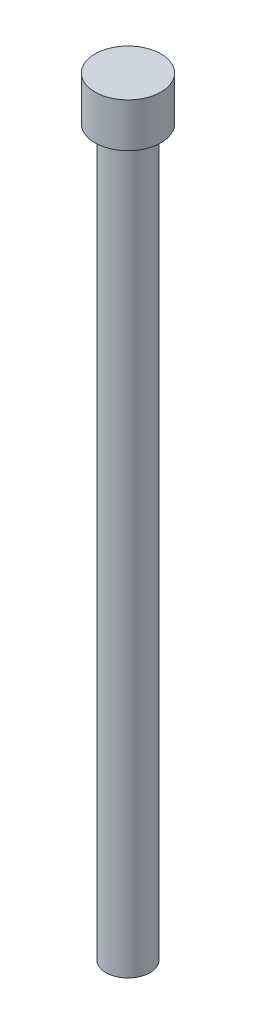
SolidWorks part; units mm, degrees
ref_plane "前视基准面" through (0, 0, 0) normal (0, 0, 1) x (1, 0, 0)
ref_plane "上视基准面" through (0, 0, 0) normal (0, 1, 0) x (1, 0, 0)
ref_plane "右视基准面" through (0, 0, 0) normal (1, 0, 0) x (0, 0, -1)
sketch "草图1" plane through (0, 0, 0) normal (0, 1, 0) x (1, 0, 0)
  circle A0 centre (0, 0) radius 2
  dimension "D1" = 4
extrude "凸台-拉伸1" add sketch "草图1" along normal blind 65.8
sketch "草图2" plane through (0, 65.8, 0) normal (0, 1, 0) x (1, 0, 0)
  circle A0 centre (0, 0) radius 3
  dimension "D1" = 6
extrude "凸台-拉伸2" add sketch "草图2" along normal blind 4
